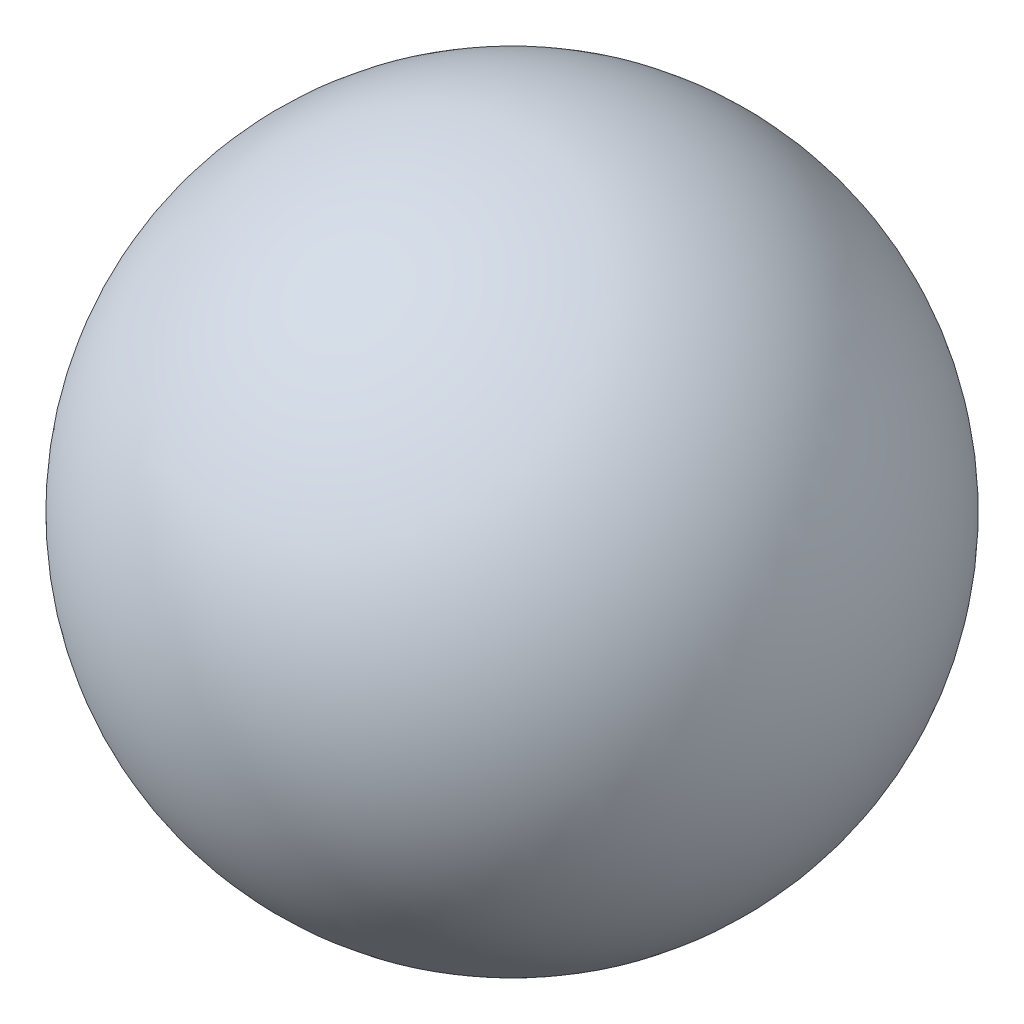
SolidWorks part; units mm, degrees
ref_plane "Front Plane" through (0, 0, 0) normal (0, 0, 1) x (1, 0, 0)
ref_plane "Top Plane" through (0, 0, 0) normal (0, 1, 0) x (1, 0, 0)
ref_plane "Right Plane" through (0, 0, 0) normal (1, 0, 0) x (0, 0, -1)
sketch "Sketch1" plane through (0, 0, 0) normal (0, 0, 1) x (1, 0, 0)
  line L0 (0, 9.8514) -> (0, -6.1486) construction
  circle A1 centre (0, 1.8514) radius 8
  dimension "D1" = 16
revolve "Revolve11" add sketch "Sketch1" angle 360 mid plane about L0
equation "\"15ز5\"=61.0198"
